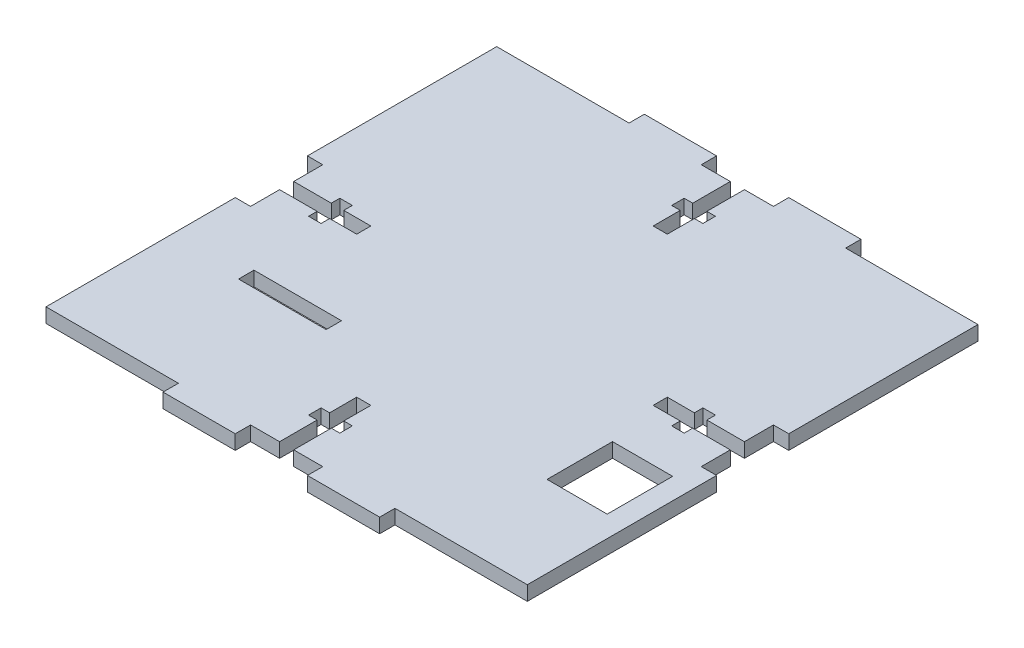
SolidWorks part; units mm, degrees
ref_plane "Front Plane" through (0, 0, 0) normal (0, 0, 1) x (1, 0, 0)
ref_plane "Top Plane" through (0, 0, 0) normal (0, 1, 0) x (1, 0, 0)
ref_plane "Right Plane" through (0, 0, 0) normal (1, 0, 0) x (0, 0, -1)
sketch "Sketch1" plane through (0, 0, 0) normal (0, 1, 0) x (1, 0, 0)
  line L1 (-50, 50) -> (50, 50)
  line L2 (-50, 50) -> (-50, -50)
  line L3 (-50, -50) -> (50, -50)
  line L4 (50, 50) -> (50, -50)
  line L5 (-50, 50) -> (50, -50) construction
  line L6 (-50, -50) -> (50, 50) construction
  point P0 (0, 0)
  dimension "D1" = 100
  dimension "D2" = 100
extrude "Boss-Extrude1" add sketch "Sketch1" along normal mid plane 3
sketch "Sketch2" plane through (0, 1.5, 0) normal (0, 1, 0) x (1, 0, 0)
  line L0 (-7.5, -50) -> (-7.5, -46.82)
  line L1 (-50, -50) -> (50, -50) construction
  line L2 (-7.5, -46.82) -> (-1.47, -46.82)
  line L3 (-1.47, -46.82) -> (-1.47, -39.02)
  line L4 (-1.47, -39.02) -> (-3.25, -39.02)
  line L5 (-3.25, -39.02) -> (-3.25, -36.42)
  line L6 (-3.25, -36.42) -> (-1.47, -36.42)
  line L7 (-1.47, -36.42) -> (-1.47, -30.8)
  line L8 (-1.47, -30.8) -> (1.47, -30.8)
  line L9 (1.47, -30.8) -> (1.47, -36.42)
  line L10 (1.47, -36.42) -> (3.25, -36.42)
  line L11 (3.25, -36.42) -> (3.25, -39.02)
  line L12 (3.25, -39.02) -> (1.47, -39.02)
  line L13 (1.47, -39.02) -> (1.47, -46.82)
  line L14 (1.47, -46.82) -> (7.5, -46.82)
  line L15 (7.5, -46.82) -> (7.5, -50)
  line L16 (0, -30.8) -> (0, -50) construction
  line L17 (-7.5, -50) -> (7.5, -50)
  line L19 (-50, 50) -> (-50, -50) construction
  line L20 (50, -50) -> (50, 50) construction
  dimension "D1" = 2.94
  dimension "D2" = 7.8
  dimension "D3" = 5.62
  dimension "D4" = 2.6
  dimension "D5" = 3.18
  dimension "D6" = 15
  dimension "D7" = 6.5
extrude "Cut-Extrude6" cut sketch "Sketch2" against normal through all
mirror "Mirror1" about plane through (0, 0, 0) normal (0, 0, 1) of "Cut-Extrude6"
sketch "Sketch3" plane through (0, 1.5, 0) normal (0, 1, 0) x (1, 0, 0)
  line L0 (0, 0) -> (-50, 0) construction
  line L1 (-50, 50) -> (-50, -50) construction
  line L2 (-50, -7.5) -> (-46.82, -7.5)
  line L3 (-46.82, -7.5) -> (-46.82, -22.5)
  line L4 (-46.82, -22.5) -> (-50, -22.5)
  line L5 (-50, -22.5) -> (-50, -7.5)
  line L7 (-50, -50) -> (-7.5, -50) construction
  dimension "D1" = 15
  dimension "D2" = 3.18
  dimension "D3" = 27.5
  dimension "D4" = 7.5
extrude "Cut-Extrude7" [suppressed] cut sketch "Sketch3" against normal blind 3
mirror "Mirror2" [suppressed] about plane through (0, 0, 0) normal (0, 0, 1)
mirror "Mirror3" [suppressed] about plane through (0, 0, 0) normal (1, 0, 0)
sketch "Sketch4" plane through (0, 1.5, 0) normal (0, 1, 0) x (1, 0, 0)
  line L0 (-22.5, 50) -> (-22.5, 46.82)
  line L1 (-7.5, 50) -> (-50, 50) construction
  line L2 (-22.5, 46.82) -> (-50, 46.82)
  line L3 (-50, 50) -> (-50, -50) construction
  line L4 (-7.5, 46.82) -> (-7.5, 50) construction
  line L6 (-50, 46.82) -> (-50, 50)
  line L7 (-50, 50) -> (-22.5, 50)
  dimension "D1" = 15
extrude "Cut-Extrude9" cut sketch "Sketch4" against normal blind 3
sketch "Sketch5" plane through (0, -1.5, 0) normal (0, -1, 0) x (1, 0, 0)
  line L0 (50, -7.5) -> (50, 7.5)
  line L1 (50, 50) -> (50, -50) construction
  line L2 (50, 7.5) -> (46.82, 7.5)
  line L3 (46.82, 7.5) -> (46.82, 1.47)
  line L4 (46.82, 1.47) -> (39.02, 1.47)
  line L5 (39.02, 1.47) -> (39.02, 3.25)
  line L6 (39.02, 3.25) -> (36.42, 3.25)
  line L7 (36.42, 3.25) -> (36.42, 1.47)
  line L8 (36.42, 1.47) -> (30.8, 1.47)
  line L9 (30.8, 1.47) -> (30.8, -1.47)
  line L10 (30.8, -1.47) -> (36.42, -1.47)
  line L11 (36.42, -1.47) -> (36.42, -3.25)
  line L12 (36.42, -3.25) -> (39.02, -3.25)
  line L13 (39.02, -3.25) -> (39.02, -1.47)
  line L14 (39.02, -1.47) -> (46.82, -1.47)
  line L15 (46.82, -1.47) -> (46.82, -7.5)
  line L16 (46.82, -7.5) -> (50, -7.5)
  line L17 (-7.5, 46.82) -> (-7.5, 50) construction
  line L18 (7.5, 46.82) -> (1.47, 46.82) construction
  line L19 (-3.25, 36.42) -> (-3.25, 39.02) construction
  line L20 (-1.47, 36.42) -> (-3.25, 36.42) construction
  line L21 (1.47, 30.8) -> (-1.47, 30.8) construction
  line L22 (-1.47, 30.8) -> (-1.47, 36.42) construction
  line L23 (1.47, 46.82) -> (1.47, 39.02) construction
  line L24 (0, 0) -> (-51.7183, 0) construction
  line L25 (30.8, 0) -> (50, 0) construction
extrude "Cut-Extrude10" cut sketch "Sketch5" against normal blind 3 contours L16 L0 L2 L3 L4 L5 L6 L7 L8 L9 L10 L11 L12 L13 L14 L15
mirror "Mirror6" about plane through (0, 0, 0) normal (1, 0, 0) of "Cut-Extrude10"
sketch "Sketch8" [suppressed] plane through (0, -1.5, 0) normal (0, -1, 0) x (1, 0, 0)
  line L0 (7.5, 46.82) -> (75, 46.82)
  line L1 (75, 50) -> (75, 22.5) construction
  line L2 (75, 46.82) -> (75, 50)
  line L3 (75, 50) -> (7.5, 50)
  line L4 (7.5, 50) -> (7.5, 46.82)
extrude "Cut-Extrude13" [suppressed] cut sketch "Sketch8" against normal blind 3
mirror "Mirror7" [suppressed] about plane through (0, 0, 0) normal (0, 0, 1)
sketch "Sketch9" [suppressed] plane through (0, -1.5, 0) normal (0, -1, 0) x (1, 0, 0)
  line L6 (-7.5, -46.82) -> (-7.5, -50) construction
  line L7 (7.5, -50) -> (7.5, -46.82) construction
  line L9 (50, -46.82) -> (22.5, -46.82)
  line L10 (50, -7.5) -> (50, -50) construction
  line L11 (22.5, -46.82) -> (22.5, -50)
  line L12 (50, -50) -> (7.5, -50) construction
  line L13 (22.5, -50) -> (50, -50)
  line L14 (50, -50) -> (50, -46.82)
  dimension "D1" = 15
extrude "Cut-Extrude14" [suppressed] cut sketch "Sketch9" against normal blind 3
mirror "Mirror8" [suppressed] about plane through (0, 0, 0) normal (0, 0, 1)
mirror "Mirror9" about plane through (0, 0, 0) normal (0, 0, 1) of "Cut-Extrude9"
mirror "Mirror10" about plane through (0, 0, 0) normal (1, 0, 0) of "Mirror9", "Cut-Extrude9"
sketch "Sketch10" [suppressed] plane through (0, -1.5, 0) normal (0, -1, 0) x (1, 0, 0)
  line L0 (-46.82, -46.82) -> (-46.82, 46.82)
  line L1 (-50, -46.82) -> (-22.5, -46.82) construction
  line L2 (-50, 46.82) -> (-22.5, 46.82) construction
  line L3 (-46.82, 46.82) -> (-50, 46.82)
  line L4 (-50, 46.82) -> (-50, -46.82)
  line L5 (-50, -46.82) -> (-50, 46.82) construction
  line L6 (-50, -46.82) -> (-46.82, -46.82)
  dimension "D1" = 3.18
extrude "Cut-Extrude15" [suppressed] cut sketch "Sketch10" against normal blind 3
pattern_linear "LPattern1" [suppressed] count 2 spacing 40
sketch "Sketch19" [suppressed] plane through (0, 1.5, 0) normal (0, 1, 0) x (1, 0, 0)
  line L0 (-72, 46.82) -> (-72, -46.82) construction
  line L1 (-72, -7.5) -> (-75.6, -7.5)
  line L2 (-72, -7.5) -> (-72, 7.5)
  line L3 (-72, 7.5) -> (-75.6, 7.5)
  line L4 (-75.6, -7.5) -> (-75.6, 7.5)
  line L5 (-75.6, 0) -> (-72, 0) construction
  line L6 (-72, -46.82) -> (72, -46.82) construction
  line L7 (72, 46.82) -> (-72, 46.82) construction
  line L8 (-72, 46.82) -> (-72, -46.82) construction
  circle A0 centre (-73.59, 0) radius 1.47
  dimension "D3" = 2.94
  dimension "D1" = 15
  dimension "D2" = 3.6
  dimension "D4" = 1.59
extrude "Boss-Extrude2" [suppressed] add sketch "Sketch19" against normal through all
sketch "Sketch20" [suppressed] plane through (0, 1.5, 0) normal (0, 1, 0) x (1, 0, 0)
  line L0 (-72, -46.82) -> (72, -46.82) construction
  line L1 (-32.5, -46.82) -> (-47.5, -46.82)
  line L2 (-32.5, -46.82) -> (-32.5, -50.42)
  line L3 (-32.5, -50.42) -> (-47.5, -50.42)
  line L4 (-47.5, -46.82) -> (-47.5, -50.42)
  line L5 (-72, -7.5) -> (-72, -46.82) construction
  line L6 (-40, -46.82) -> (-40, -50.42) construction
  circle A0 centre (-40, -48.41) radius 1.48
  dimension "D4" = 2.96
  dimension "D1" = 24.5
  dimension "D2" = 3.6
  dimension "D3" = 15
  dimension "D5" = 1.59
extrude "Boss-Extrude3" [suppressed] add sketch "Sketch20" against normal blind 3
mirror "Mirror14" [suppressed] about plane through (0, 0, 0) normal (0, 0, 1)
pattern_linear "LPattern2" [suppressed] count 2 spacing 40
sketch "Sketch21" [suppressed] plane through (0, 1.5, 0) normal (0, 1, 0) x (1, 0, 0)
  line L0 (-71.82, -7.5) -> (-71.82, 7.5) construction
  line L1 (-71.82, 7.5) -> (-73.41, 7.5) construction
  line L2 (-71.82, 7.5) -> (-75, 7.5) construction
  circle A0 centre (-73.22, 0) radius 1.48
  dimension "D1" = 2.96
  dimension "D2" = 1.4
extrude "Cut-Extrude16" [suppressed] cut sketch "Sketch21" against normal blind 3
mirror "Mirror15" [suppressed] about plane through (0, 0, 0) normal (1, 0, 0)
mirror "Mirror16" [suppressed] about plane through (0, 0, 0) normal (1, 0, 0)
sketch "Sketch23" [suppressed] plane through (0, -1.5, 0) normal (0, -1, 0) x (1, 0, 0)
  line L0 (75, 46.82) -> (1.47, 46.82) construction
  line L1 (69, 52.82) -> (69, 46.82) construction
  line L86 (-32.5, -46.82) -> (-32.5, -50)
  line L87 (-32.5, -50) -> (-7.5, -50)
  line L88 (-7.5, -50) -> (-7.5, -46.82)
  line L89 (-7.5, -46.82) -> (-1.47, -46.82)
  line L90 (-1.47, -46.82) -> (-1.47, -39.02)
  line L91 (-1.47, -39.02) -> (-3.25, -39.02)
  line L92 (-3.25, -39.02) -> (-3.25, -36.42)
  line L93 (-3.25, -36.42) -> (-1.47, -36.42)
  line L94 (-1.47, -36.42) -> (-1.47, -30.8)
  line L95 (-1.47, -30.8) -> (1.47, -30.8)
  line L96 (1.47, -30.8) -> (1.47, -36.42)
  line L97 (1.47, -36.42) -> (3.25, -36.42)
  line L98 (3.25, -36.42) -> (3.25, -39.02)
  line L99 (3.25, -39.02) -> (1.47, -39.02)
  line L100 (1.47, -39.02) -> (1.47, -46.82)
  line L101 (1.47, -46.82) -> (7.5, -46.82)
  line L102 (7.5, -46.82) -> (7.5, -50)
  line L103 (7.5, -50) -> (75, -50)
  line L104 (75, -50) -> (75, -22.5)
  line L105 (75, -22.5) -> (71.82, -22.5)
  line L106 (71.82, -22.5) -> (71.82, -7.5)
  line L107 (71.82, -7.5) -> (75, -7.5)
  line L108 (75, -7.5) -> (75, 7.5)
  line L109 (75, 7.5) -> (71.82, 7.5)
  line L110 (71.82, 7.5) -> (71.82, 22.5)
  line L111 (71.82, 22.5) -> (75, 22.5)
  line L112 (75, 22.5) -> (75, 46.82)
  line L113 (75, 46.82) -> (1.47, 46.82)
  line L114 (1.47, 46.82) -> (1.47, 39.02)
  line L115 (1.47, 39.02) -> (3.25, 39.02)
  line L116 (3.25, 39.02) -> (3.25, 36.42)
  line L117 (3.25, 36.42) -> (1.47, 36.42)
  line L118 (1.47, 36.42) -> (1.47, 30.8)
  line L119 (1.47, 30.8) -> (-1.47, 30.8)
  line L120 (-1.47, 30.8) -> (-1.47, 36.42)
  line L121 (-1.47, 36.42) -> (-3.25, 36.42)
  line L122 (-3.25, 36.42) -> (-3.25, 39.02)
  line L123 (-3.25, 39.02) -> (-1.47, 39.02)
  line L124 (-1.47, 39.02) -> (-1.47, 46.82)
  line L125 (-1.47, 46.82) -> (-7.5, 46.82)
  line L126 (-7.5, 46.82) -> (-7.5, 50)
  line L127 (-7.5, 50) -> (-32.5, 50)
  line L128 (-32.5, 50) -> (-32.5, 46.82)
  line L129 (-32.5, 46.82) -> (-38.53, 46.82)
  line L130 (-38.53, 46.82) -> (-38.53, 39.02)
  line L131 (-38.53, 39.02) -> (-36.75, 39.02)
  line L132 (-36.75, 39.02) -> (-36.75, 36.42)
  line L133 (-36.75, 36.42) -> (-38.53, 36.42)
  line L134 (-38.53, 36.42) -> (-38.53, 30.8)
  line L135 (-38.53, 30.8) -> (-41.47, 30.8)
  line L136 (-41.47, 30.8) -> (-41.47, 36.42)
  line L137 (-41.47, 36.42) -> (-43.25, 36.42)
  line L138 (-43.25, 36.42) -> (-43.25, 39.02)
  line L139 (-43.25, 39.02) -> (-41.47, 39.02)
  line L140 (-41.47, 39.02) -> (-41.47, 46.82)
  line L141 (-41.47, 46.82) -> (-47.5, 46.82)
  line L142 (-47.5, 46.82) -> (-47.5, 50)
  line L143 (-47.5, 50) -> (-75, 50)
  line L144 (-75, 50) -> (-75, 22.5)
  line L145 (-75, 22.5) -> (-71.82, 22.5)
  line L146 (-71.82, 22.5) -> (-71.82, 7.5)
  line L147 (-71.82, 7.5) -> (-75, 7.5)
  line L148 (-75, 7.5) -> (-75, -7.5)
  line L149 (-75, -7.5) -> (-71.82, -7.5)
  line L150 (-71.82, -7.5) -> (-71.82, -22.5)
  line L151 (-71.82, -22.5) -> (-75, -22.5)
  line L152 (-75, -22.5) -> (-75, -50)
  line L153 (-75, -50) -> (-47.5, -50)
  line L154 (-47.5, -50) -> (-47.5, -46.82)
  line L155 (-47.5, -46.82) -> (-41.47, -46.82)
  line L156 (-41.47, -46.82) -> (-41.47, -39.02)
  line L157 (-41.47, -39.02) -> (-43.25, -39.02)
  line L158 (-43.25, -39.02) -> (-43.25, -36.42)
  line L159 (-43.25, -36.42) -> (-41.47, -36.42)
  line L160 (-41.47, -36.42) -> (-41.47, -30.8)
  line L161 (-41.47, -30.8) -> (-38.53, -30.8)
  line L162 (-38.53, -30.8) -> (-38.53, -36.42)
  line L163 (-38.53, -36.42) -> (-36.75, -36.42)
  line L164 (-36.75, -36.42) -> (-36.75, -39.02)
  line L165 (-36.75, -39.02) -> (-38.53, -39.02)
  line L166 (-38.53, -39.02) -> (-38.53, -46.82)
  line L167 (-38.53, -46.82) -> (-32.5, -46.82)
  line L195 (75, 46.82) -> (63, 46.82)
  arc A0 (75, 46.82) -> (63, 46.82) centre (69, 46.82) ccw
  dimension "D1" = 6
  dimension "D2" = 0
extrude "Boss-Extrude4" [suppressed] add sketch "Sketch23" against normal blind 3
sketch "Sketch24" [suppressed] plane through (0, 1.5, 0) normal (0, 1, 0) x (1, 0, 0)
  line L0 (69, -52.82) -> (69, -46.82) construction
  line L1 (75, -46.82) -> (63, -46.82) construction
  line L2 (69, -48.32) -> (69, -52.82) construction
  arc A0 (63, -46.82) -> (75, -46.82) centre (69, -46.82) ccw construction
  circle A1 centre (69, -48.32) radius 2.25
  dimension "D1" = 4.5
  dimension "D2" = 1.5
extrude "Cut-Extrude17" [suppressed] cut sketch "Sketch24" against normal blind 3
sketch "Sketch26" [suppressed] plane through (0, 1.5, 0) normal (0, 1, 0) x (1, 0, 0)
  line L0 (-28.5, 49.82) -> (-28.5, 46.82)
  line L1 (31.5, 49.82) -> (-31.5, 49.82) construction
  line L2 (-28.5, 46.82) -> (-22.5, 46.82)
  line L3 (-22.5, 46.82) -> (-22.5, 49.82)
  line L4 (-22.5, 49.82) -> (-28.5, 49.82)
  line L5 (-31.5, 49.82) -> (-31.5, -49.82) construction
  line L6 (31.5, -49.82) -> (31.5, 49.82) construction
  dimension "D1" = 3
  dimension "D2" = 3
  dimension "D3" = 54
extrude "Cut-Extrude18" [suppressed] cut sketch "Sketch26" against normal blind 3
mirror "Mirror17" [suppressed] about plane through (0, 0, 0) normal (0, 0, 1)
sketch "Sketch27" plane through (0, -1.5, 0) normal (0, -1, 0) x (1, 0, 0)
  line L0 (-50, 46.82) -> (-22.5, 46.82) construction
  line L1 (-35, 18.62) -> (-16.8, 18.62)
  line L2 (-35, 18.62) -> (-35, 21.82)
  line L3 (-35, 21.82) -> (-16.8, 21.82)
  line L4 (-16.8, 18.62) -> (-16.8, 21.82)
  line L5 (-50, 7.5) -> (-50, 46.82) construction
  dimension "D1" = 25
  dimension "D2" = 15
  dimension "D3" = 3.2
  dimension "D4" = 18.2
extrude "Cut-Extrude19" cut sketch "Sketch27" against normal blind 3
sketch "Sketch28" [suppressed] plane through (0, -1.5, 0) normal (0, -1, 0) x (-1, 0, 0)
  line L1 (35, -18.62) -> (16.8, -18.62)
  line L2 (35, -18.62) -> (35, -21.82)
  line L3 (35, -21.82) -> (16.8, -21.82)
  line L4 (16.8, -18.62) -> (16.8, -21.82)
  line L6 (46.82, -46.82) -> (22.5, -46.82) construction
  line L7 (46.82, 46.82) -> (46.82, -46.82) construction
  dimension "D1" = 3.2
  dimension "D2" = 11.82
  dimension "D3" = 18.2
  dimension "D4" = 25
extrude "Cut-Extrude20" [suppressed] cut sketch "Sketch28" against normal blind 3
sketch "Sketch37" [suppressed] plane through (0, -1.5, 0) normal (0, -1, 0) x (-1, 0, 0)
  line L0 (72, -7.5) -> (72, -46.82) construction
  line L1 (72, -46.82) -> (47.5, -46.82) construction
  line L3 (50, 31.48) -> (50, -16.82) construction
  line L6 (0.8, 16.18) -> (0.8, -11.72) construction
  circle A0 centre (51.6, 31.48) radius 1.6
  circle A1 centre (0.8, 16.18) radius 1.6
  circle A2 centre (50, -16.82) radius 1.6
  circle A3 centre (0.8, -11.72) radius 1.6
  dimension "D1" = 3.2
  dimension "D2" = 22
  dimension "D3" = 30
  dimension "D4" = 48.3
  dimension "D5" = 5.1
  dimension "D6" = 27.9
  dimension "D7" = 50.8
extrude "Cut-Extrude29" [suppressed] cut sketch "Sketch37" against normal blind 3
sketch "Sketch38" plane through (0, 1.5, 0) normal (0, 1, 0) x (1, 0, 0)
  line L0 (50, -46.82) -> (50, -7.5) construction
  line L1 (34.1, -25.82) -> (46.7, -25.82)
  line L2 (34.1, -25.82) -> (34.1, -12.32)
  line L3 (34.1, -12.32) -> (46.7, -12.32)
  line L4 (46.7, -25.82) -> (46.7, -12.32)
  line L5 (50, -46.82) -> (22.5, -46.82) construction
  dimension "D1" = 13.5
  dimension "D2" = 12.6
  dimension "D3" = 3.3
  dimension "D4" = 21
extrude "Boss-Extrude5" add sketch "Sketch38" against normal blind 3
sketch "Sketch39" plane through (0, 1.5, 0) normal (0, 1, 0) x (1, 0, 0)
  line L0 (50, -46.82) -> (22.5, -46.82) construction
  line L1 (33.1, -25.82) -> (45.6, -25.82)
  line L2 (33.1, -25.82) -> (33.1, -12.22)
  line L3 (33.1, -12.22) -> (45.6, -12.22)
  line L4 (45.6, -25.82) -> (45.6, -12.22)
  line L5 (50, -46.82) -> (50, -7.5) construction
  dimension "D1" = 13.6
  dimension "D2" = 12.5
  dimension "D3" = 21
  dimension "D4" = 4.4
extrude "Cut-Extrude30" cut sketch "Sketch39" against normal blind 3
sketch "Sketch40" [suppressed] plane through (0, 1.5, 0) normal (0, 1, 0) x (1, 0, 0)
  circle A0 centre (33.8876, -2.1948) radius 1.4
  circle A1 centre (55.3876, 11.5552) radius 1.4
  circle A2 centre (33.8876, 25.3052) radius 1.4
extrude "Cut-Extrude31" [suppressed] cut sketch "Sketch40" against normal blind 3
